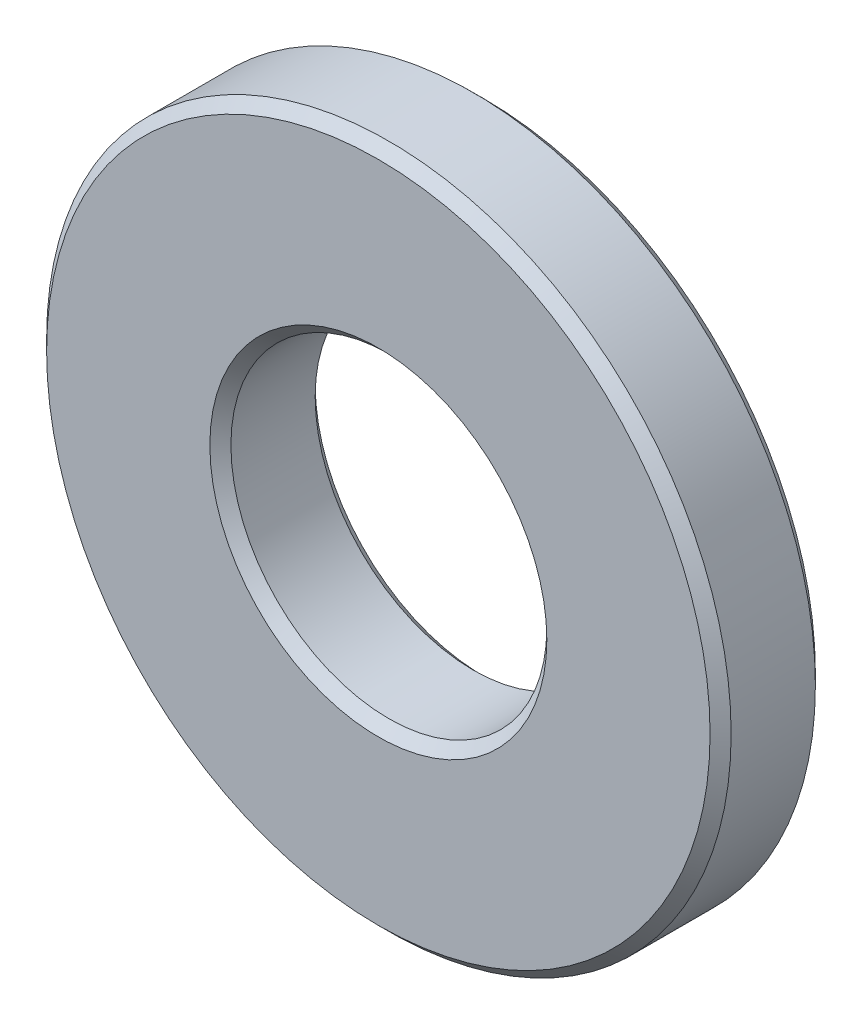
SolidWorks part; units mm, degrees
ref_plane "前视基准面" through (0, 0, 0) normal (0, 0, 1) x (1, 0, 0)
ref_plane "上视基准面" through (0, 0, 0) normal (0, 1, 0) x (1, 0, 0)
ref_plane "右视基准面" through (0, 0, 0) normal (1, 0, 0) x (0, 0, -1)
sketch "Sketch1" plane through (0, 0, 0) normal (0, 0, 1) x (1, 0, 0)
  circle A0 centre (0, 0) radius 15
  circle A1 centre (0, 0) radius 32.5
  dimension "D1" = 65
  dimension "D2" = 30
extrude "Extrude1" add sketch "Sketch1" along normal mid plane 10
cosmetic thread "Cosmetic Thread1" parameters "D2"=90
chamfer "Chamfer2" distance 1 angle 45 4 edges at (15, 0, -5) (32.5, 0, -5) (32.5, 0, 5) (15, 0, 5)
